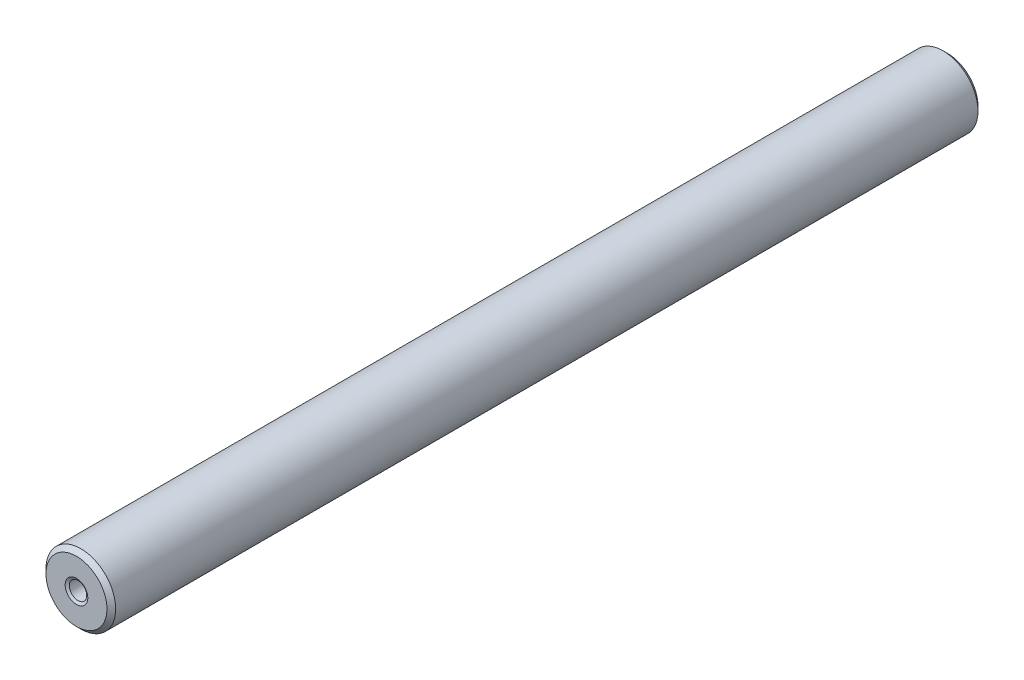
SolidWorks part; units mm, degrees
ref_plane "Front Plane" through (0, 0, 0) normal (0, 0, 1) x (1, 0, 0)
ref_plane "Top Plane" through (0, 0, 0) normal (0, 1, 0) x (1, 0, 0)
ref_plane "Right Plane" through (0, 0, 0) normal (1, 0, 0) x (0, 0, -1)
sketch "Sketch1" plane through (0, 0, 0) normal (0, 1, 0) x (1, 0, 0)
  line L0 (0, 0) -> (0, -100) construction
  line L1 (0, 0) -> (-4, 0) construction
  line L2 (-4, 0) -> (-4, -100) construction
  line L3 (-4, -100) -> (0, -100) construction
  line L4 (-1, 0) -> (-1, -100) construction
  line L5 (0, -2) -> (-4, -2) construction
  line L6 (-1, 0) -> (-4, 0)
  line L7 (0, -50) -> (-4, -50) construction
  line L8 (0, -2) -> (-1, -2)
  line L9 (-1, -2) -> (-1, 0)
  line L10 (0, -98) -> (-1, -98)
  line L11 (-1, -98) -> (-1, -100)
  line L12 (-4, 0) -> (-4, -100)
  line L13 (-4, -100) -> (-1, -100)
  line L14 (0, -98) -> (0, -2)
  dimension "D1" = 100
  dimension "D2" = 4
  dimension "D3" = 1
  dimension "D4" = 2
revolve "Revolve1" add sketch "Sketch1" angle 360 about L14
chamfer "Chamfer1" distance 0.5 angle 45 2 edges at (4, 0, 0) (4, 0, 100)
chamfer "Chamfer2" distance 0.3 angle 30 4 edges at (1, 0, 2) (1, 0, 0) (1, 0, 98) (1, 0, 100)
